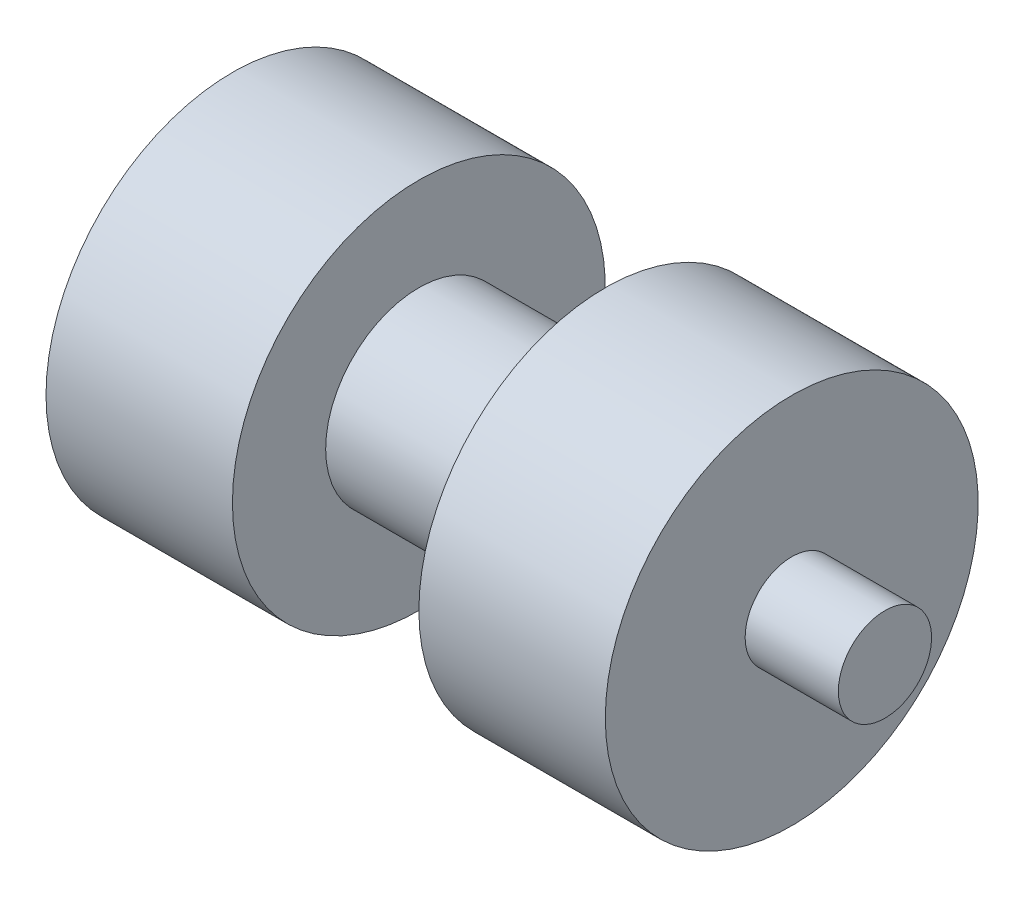
SolidWorks part; units mm, degrees
ref_plane "Front Plane" through (0, 0, 0) normal (0, 0, 1) x (1, 0, 0)
ref_plane "Top Plane" through (0, 0, 0) normal (0, 1, 0) x (1, 0, 0)
ref_plane "Right Plane" through (0, 0, 0) normal (1, 0, 0) x (0, 0, -1)
sketch "Sketch3" plane through (0, 0, 0) normal (0, 0, 1) x (1, 0, 0)
  line L0 (-20, 0) -> (20, 0)
  line L1 (-20, 0) -> (-20, 2.5)
  line L2 (-20, 2.5) -> (-15, 2.5)
  line L3 (-15, 2.5) -> (-15, 10)
  line L4 (-15, 10) -> (-5, 10)
  line L5 (15, 10) -> (15, 2.5)
  line L6 (15, 2.5) -> (20, 2.5)
  line L7 (20, 2.5) -> (20, 0)
  line L8 (-5, 5) -> (5, 5)
  line L9 (-5, 10) -> (-5, 5)
  line L11 (5, 5) -> (5, 10)
  line L12 (5, 10) -> (15, 10)
  dimension "D1" = 2.5
  dimension "D2" = 20
  dimension "D3" = 10
  dimension "D4" = 5
  dimension "D5" = 5
  dimension "D6" = 40
  dimension "D7" = 10
  dimension "D8" = 10
  dimension "D9" = 5
revolve "Revolve1" add sketch "Sketch3" angle 360 about L0
